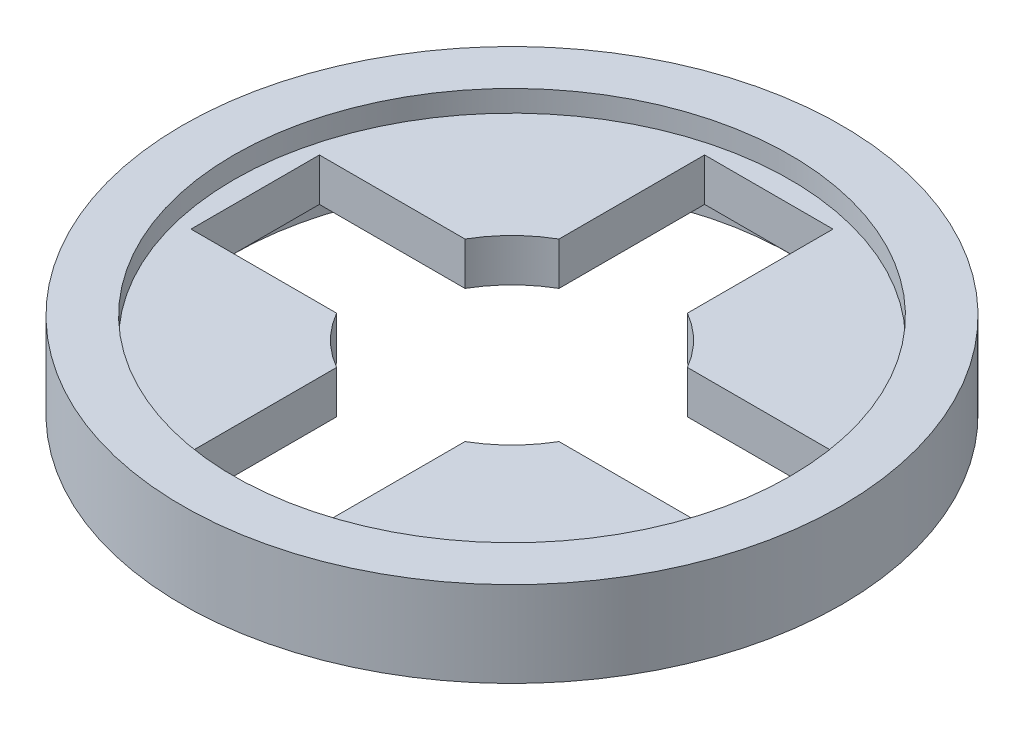
SolidWorks part; units mm, degrees
material "2.0371 (CuZn38Pb2)"
ref_plane "Plan de face" through (0, 0, 0) normal (0, 0, 1) x (1, 0, 0)
ref_plane "Plan de dessus" through (0, 0, 0) normal (0, 1, 0) x (1, 0, 0)
ref_plane "Plan de droite" through (0, 0, 0) normal (1, 0, 0) x (0, 0, -1)
sketch "base" plane through (0, 0, 0) normal (0, 0, 1) x (1, 0, 0)
  line L0 (0, -0.5) -> (0, 0.5) construction
  line L1 (1.5, 0.5) -> (4, 0.5)
  line L2 (1.5, 0.5) -> (1.5, -0.5)
  line L3 (1.5, -0.5) -> (4, -0.5)
  line L4 (4, 0.5) -> (4, -0.5)
  line L5 (0, 0) -> (1.5, 0) construction
  line L6 (1.5, 0) -> (4, 0) construction
  point P8 (0, 0)
  dimension "W" = 2.5
  dimension "H" = 1
  dimension "R" = 1.5
revolve "Revolution" add sketch "base" angle 360 about L0
sketch "Sketch1" plane through (0, -0.5, 0) normal (0, -1, 0) x (-1, 0, 0)
  circle A0 centre (0, 0) radius 3.85
  circle A1 centre (0, 0) radius 4
  dimension "D1" = 7.7
extrude "Cut-Extrude1" cut sketch "Sketch1" against normal blind 10
sketch "Sketch6" plane through (0, -0.5, 0) normal (0, -1, 0) x (-1, 0, 0)
  circle A0 centre (0, 0) radius 3.25
  dimension "D1" = 6.5
extrude "Cut-Extrude5" cut sketch "Sketch6" against normal blind 0.25
sketch "Sketch7" plane through (0, 0.5, 0) normal (0, 1, 0) x (1, 0, 0)
  circle A0 centre (0, 0) radius 3.25
  dimension "D1" = 6.5
extrude "Cut-Extrude6" cut sketch "Sketch7" against normal blind 0.25
sketch "Sketch4" plane through (0, -0.5, 0) normal (0, -1, 0) x (-1, 0, 0)
  line L1 (-3, 0.75) -> (3, 0.75)
  line L2 (-3, 0.75) -> (-3, -0.75)
  line L3 (-3, -0.75) -> (3, -0.75)
  line L4 (3, 0.75) -> (3, -0.75)
  line L5 (-3, 0.75) -> (3, -0.75) construction
  line L6 (-3, -0.75) -> (3, 0.75) construction
  line L7 (-0.75, 3) -> (0.75, 3)
  line L8 (-0.75, 3) -> (-0.75, -3)
  line L9 (-0.75, -3) -> (0.75, -3)
  line L10 (0.75, 3) -> (0.75, -3)
  line L11 (-0.75, 3) -> (0.75, -3) construction
  line L12 (-0.75, -3) -> (0.75, 3) construction
  point P0 (0, 0)
  point P6 (0, 0)
  dimension "D1" = 6
  dimension "D2" = 1.5
  dimension "D3" = 1.5
  dimension "D4" = 6
extrude "Cut-Extrude4" cut sketch "Sketch4" against normal blind 10
equation "\"R@base\"= \"magnet_H\" / 2"
equation "\"W@base\" =  ( \"magnet_DE\" - \"magnet_DI\" )  / 2"
equation "\"H@base\" = \"gap_magnet_H\""
equation "\"magnet_DI\"= 3mm'inner diameter of the o-ring magnet"
equation "\"magnet_DE\"= 8mm'external diameter of the o-ring magnet"
equation "\"magnet_H\"= 3mm'tall of the magnet"
equation "\"gap_magnet_H\"= 1mm'gap between the 2 magnets"
equation "\"plug_DI\"= 1.5mm'size of the inner extrude of the plug (finger contact)"
